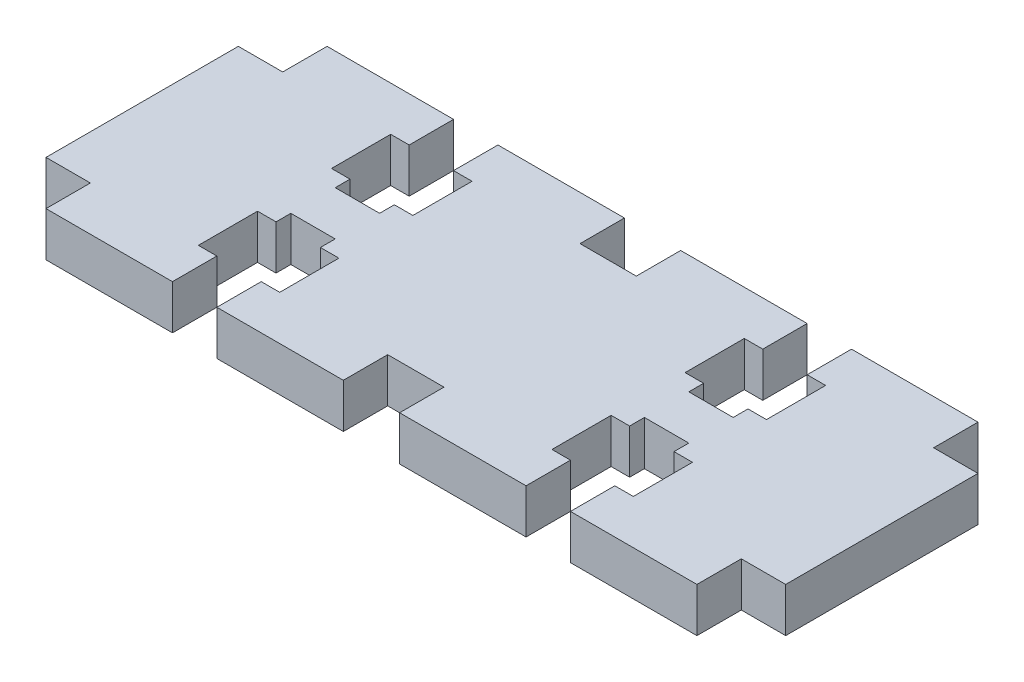
SolidWorks part; units mm, degrees
ref_plane "前视基准面" through (0, 0, 0) normal (0, 0, 1) x (1, 0, 0)
ref_plane "上视基准面" through (0, 0, 0) normal (0, 1, 0) x (1, 0, 0)
ref_plane "右视基准面" through (0, 0, 0) normal (1, 0, 0) x (0, 0, -1)
other "Configuration Table"
sketch "草图1" plane through (0, 0, 0) normal (0, 1, 0) x (1, 0, 0)
  line L0 (25, 0) -> (25, -13)
  line L1 (0, 0) -> (50, 0)
  line L2 (0, 0) -> (0, -13)
  line L3 (0, -13) -> (50, -13)
  line L4 (50, 0) -> (50, -13)
  line L5 (3, -13) -> (23.0981, -13)
  line L6 (3, -13) -> (3, -16)
  line L7 (3, -16) -> (23.0981, -16)
  line L8 (23.0981, -13) -> (23.0981, -16)
  line L13 (38.4509, -8) -> (35.4509, -8)
  line L14 (11.5491, -16) -> (14.5491, -16)
  line L19 (11.5491, -16) -> (11.5491, -8)
  line L20 (11.5491, -8) -> (14.5491, -8)
  line L33 (0, -6.5) -> (50, -6.5)
  line L54 (3, 3) -> (23.0981, 3)
  line L55 (23.0981, 0) -> (23.0981, 3)
  line L56 (3, 0) -> (23.0981, 0)
  line L57 (3, 0) -> (3, 3)
  line L58 (14.5491, -16) -> (14.5491, -8)
  line L59 (10.2991, -9) -> (15.7991, -9)
  line L60 (10.2991, -9) -> (10.2991, -13)
  line L61 (10.2991, -13) -> (15.7991, -13)
  line L62 (15.7991, -9) -> (15.7991, -13)
  line L63 (35.4509, -16) -> (35.4509, -8)
  line L64 (38.4509, -16) -> (35.4509, -16)
  line L65 (38.4509, -16) -> (38.4509, -8)
  line L66 (39.7009, -13) -> (34.2009, -13)
  line L67 (34.2009, -9) -> (34.2009, -13)
  line L68 (39.7009, -9) -> (34.2009, -9)
  line L69 (39.7009, -9) -> (39.7009, -13)
  line L70 (39.7009, -4) -> (39.7009, 0)
  line L71 (39.7009, -4) -> (34.2009, -4)
  line L72 (34.2009, -4) -> (34.2009, 0)
  line L73 (39.7009, 0) -> (34.2009, 0)
  line L74 (38.4509, 3) -> (38.4509, -5)
  line L75 (38.4509, 3) -> (35.4509, 3)
  line L76 (35.4509, 3) -> (35.4509, -5)
  line L77 (38.4509, -5) -> (35.4509, -5)
  line L78 (10.2991, 0) -> (15.7991, 0)
  line L79 (15.7991, -4) -> (15.7991, 0)
  line L80 (10.2991, -4) -> (15.7991, -4)
  line L81 (10.2991, -4) -> (10.2991, 0)
  line L82 (11.5491, -5) -> (14.5491, -5)
  line L83 (14.5491, 3) -> (14.5491, -5)
  line L84 (11.5491, 3) -> (14.5491, 3)
  line L85 (11.5491, 3) -> (11.5491, -5)
  line L86 (47, -16) -> (26.9019, -16)
  line L87 (26.9019, -13) -> (26.9019, -16)
  line L88 (47, -13) -> (26.9019, -13)
  line L89 (47, -13) -> (47, -16)
  line L90 (47, 0) -> (47, 3)
  line L91 (47, 0) -> (26.9019, 0)
  line L92 (26.9019, 0) -> (26.9019, 3)
  line L93 (47, 3) -> (26.9019, 3)
  point P15 (13.0491, -16)
  dimension "D3" = 3
  dimension "D4" = 8
  dimension "D1" = 50
  dimension "D2" = 13
  dimension "D6" = 4
  dimension "D7" = 3
  dimension "D8" = 3
  dimension "D9" = 2.75
  dimension "D10" = 0
  dimension "D11" = 1.5
  dimension "D5" = 5.5
extrude "凸台-拉伸1" add sketch "草图1" along normal blind 3
